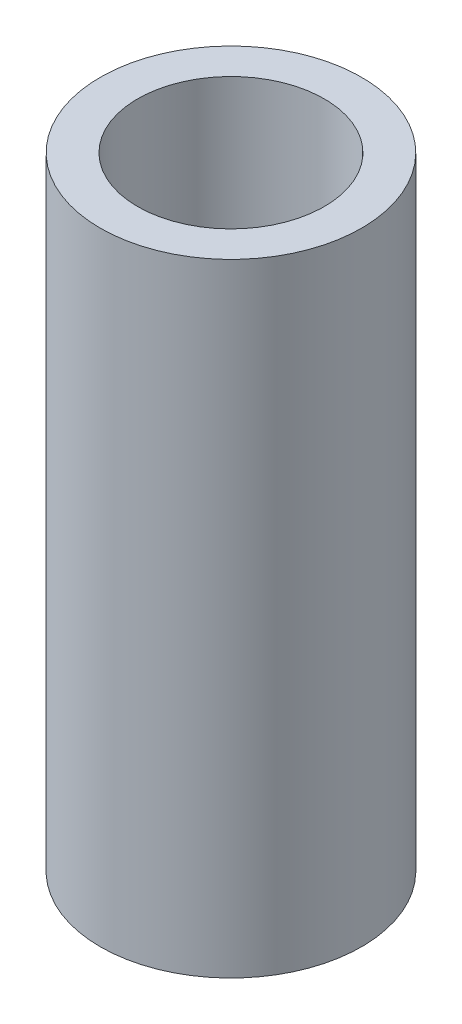
SolidWorks part; units mm, degrees
ref_plane "Спереди" through (0, 0, 0) normal (0, 0, 1) x (1, 0, 0)
ref_plane "Сверху" through (0, 0, 0) normal (0, 1, 0) x (1, 0, 0)
ref_plane "Справа" through (0, 0, 0) normal (1, 0, 0) x (0, 0, -1)
sketch "Эскиз1" plane through (0, 0, 0) normal (0, 1, 0) x (1, 0, 0)
  circle A0 centre (0, 0) radius 10.5
extrude "Вытянуть1" add sketch "Эскиз1" along normal blind 50
sketch "Эскиз2" plane through (0, 50, 0) normal (0, 1, 0) x (1, 0, 0)
  circle A0 centre (0, 0) radius 7.5
extrude "Вытянуть2" cut sketch "Эскиз2" against normal blind 20
